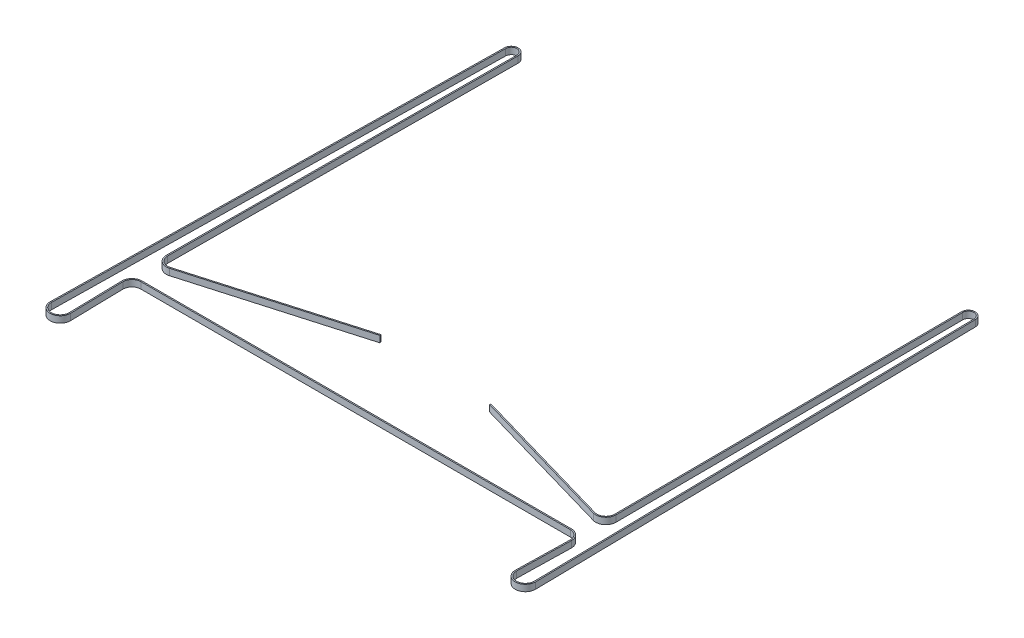
SolidWorks part; units mm, degrees
ref_plane "Front Plane" through (0, 0, 0) normal (0, 0, 1) x (1, 0, 0)
ref_plane "Top Plane" through (0, 0, 0) normal (0, 1, 0) x (1, 0, 0)
ref_plane "Right Plane" through (0, 0, 0) normal (1, 0, 0) x (0, 0, -1)
ref_plane "Plane1" through (0, 98.1376, 0) normal (0, 1, 0) x (1, 0, 0)
sketch "Sketch1" plane through (0, 0, 0) normal (0, 1, 0) x (1, 0, 0)
  line L0 (476.8725, -81.4029) -> (484.0318, -521.5921)
  line L1 (466.535, -521.545) -> (467.674, -468.9186)
  line L2 (465.7488, -81.5246) -> (467.6762, -424.8273)
  line L3 (457.7263, -458.7533) -> (217.9548, -458.7533)
  line L4 (37.4885, -434.4442) -> (198.4564, -388.0632)
  line L5 (246.23, -12.3063) -> (246.23, 12.3063) construction
  line L6 (246.23, -327.9877) -> (246.23, -29.8379) construction
  line L7 (25.925, -521.545) -> (24.786, -468.9186)
  line L8 (15.5875, -81.4029) -> (8.4282, -521.5921)
  line L9 (26.7112, -81.5246) -> (24.7838, -424.8273)
  line L10 (34.7337, -458.7533) -> (217.9548, -458.7533)
  line L11 (454.9715, -434.4442) -> (311.3842, -393.0712)
  circle A1 centre (475.2829, -521.7344) radius 8.75 construction
  circle A2 centre (457.7263, -468.7033) radius 8.75 construction
  circle A3 centre (457.7263, -468.7033) radius 8.75 construction
  circle A4 centre (475.2829, -521.7344) radius 8.75
  circle A5 centre (457.7263, -424.8832) radius 8.75 construction
  arc A6 (466.6098, -84.3778) -> (467.5641, -85.5151) centre (471.31, -81.4029) ccw construction
  circle A7 centre (471.31, -81.4029) radius 5.5625 construction
  arc A8 (484.0318, -521.5921) -> (466.535, -521.545) centre (475.2829, -521.7344) cw
  arc A9 (467.674, -468.9186) -> (457.7263, -458.7533) centre (457.7263, -468.7033) ccw
  arc A10 (476.8725, -81.4029) -> (465.7488, -81.5246) centre (471.311, -81.4934) ccw
  arc A11 (467.6762, -424.8273) -> (454.9715, -434.4442) centre (457.7263, -424.8832) cw
  circle A14 centre (34.7337, -468.7033) radius 9.95 construction
  arc A15 (8.4282, -521.5921) -> (25.925, -521.545) centre (17.1771, -521.7344) ccw
  arc A16 (15.5875, -81.4029) -> (26.7112, -81.5246) centre (21.149, -81.4934) cw
  arc A17 (24.7838, -424.8273) -> (37.4885, -434.4442) centre (34.7337, -424.8832) ccw
  arc A18 (24.786, -468.9186) -> (34.7337, -458.7533) centre (34.7337, -468.7033) cw
  circle A19 centre (471.31, -81.4029) radius 8 construction
  circle A20 centre (471.31, -81.4029) radius 8
  circle A21 centre (471.31, -81.4029) radius 8 construction
  circle A22 centre (471.31, -81.4029) radius 8
  circle A23 centre (457.7263, -424.8832) radius 8.75 construction
  dimension "D2" = 1.2
  dimension "D1" = 1.2
  dimension "D3" = 0
extrude "Extrude-Thin1" add sketch "Sketch1" along normal blind 6.35 from surface at 98.1376 thin contours A11 L2 A10 L0 A8 L1 A9 L3 starting at plane "Plane1" thin type one direction reverse wall 1.2
